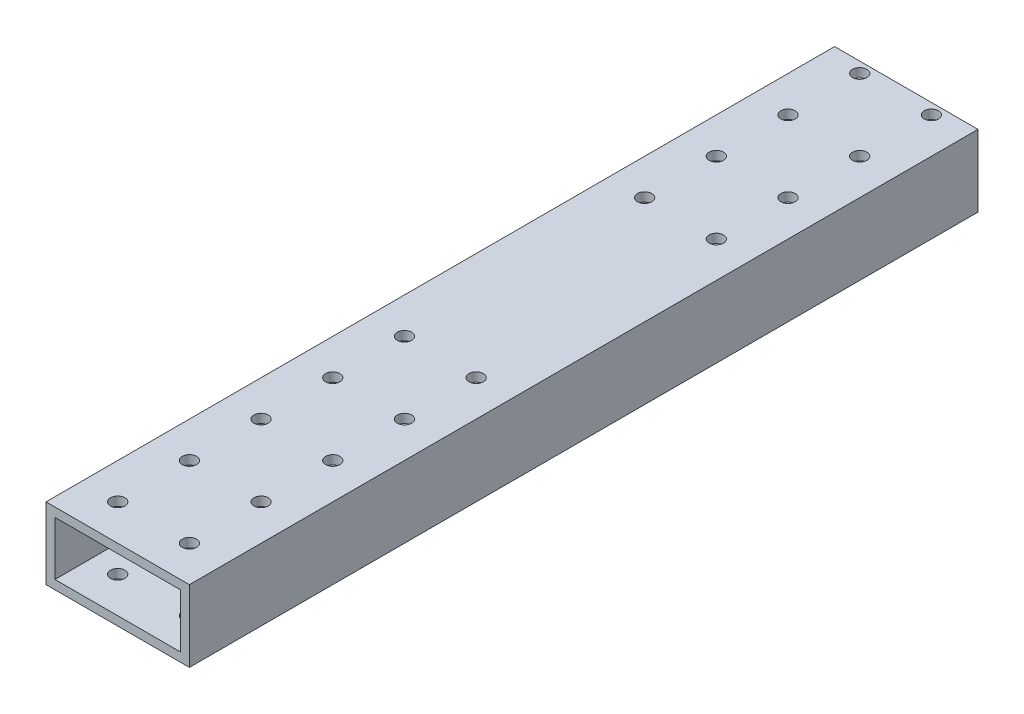
SolidWorks part; units mm, degrees
ref_plane "Front Plane" through (0, 0, 0) normal (0, 0, 1) x (1, 0, 0)
ref_plane "Top Plane" through (0, 0, 0) normal (0, 1, 0) x (1, 0, 0)
ref_plane "Right Plane" through (0, 0, 0) normal (1, 0, 0) x (0, 0, -1)
sketch "Sketch1" plane through (0, 0, 0) normal (0, 0, 1) x (1, 0, 0)
  line L1 (-25.4, -12.7) -> (25.4, -12.7)
  line L2 (-25.4, -12.7) -> (-25.4, 12.7)
  line L3 (-25.4, 12.7) -> (25.4, 12.7)
  line L4 (25.4, -12.7) -> (25.4, 12.7)
  line L5 (-25.4, -12.7) -> (25.4, 12.7) construction
  line L6 (-25.4, 12.7) -> (25.4, -12.7) construction
  line L7 (-22.225, -9.525) -> (22.225, -9.525)
  line L8 (-22.225, -9.525) -> (-22.225, 9.525)
  line L9 (-22.225, 9.525) -> (22.225, 9.525)
  line L10 (22.225, -9.525) -> (22.225, 9.525)
  line L11 (-22.225, -9.525) -> (22.225, 9.525) construction
  line L12 (-22.225, 9.525) -> (22.225, -9.525) construction
  point P0 (0, 0)
  point P6 (0, 0)
  dimension "D1" = 50.8
  dimension "D2" = 25.4
  dimension "D3" = 44.45
  dimension "D4" = 19.05
extrude "Boss-Extrude1" add sketch "Sketch1" along normal blind 279.4
sketch "Sketch2" plane through (0, 12.7, 0) normal (0, 1, 0) x (1, 0, 0)
  line L0 (-25.4, -139.7) -> (25.4, -139.7) construction
  line L1 (-25.4, -279.4) -> (-25.4, 0) construction
  line L2 (25.4, -279.4) -> (25.4, 0) construction
  line L3 (25.4, 0) -> (-25.4, 0) construction
  line L5 (25.4, -279.4) -> (-25.4, -279.4) construction
  circle A0 centre (-12.7, -3.81) radius 2.54
  circle A12 centre (-12.7, -266.7) radius 2.54
  circle A13 centre (12.7, -266.7) radius 2.54
  circle A14 centre (12.7, -241.3) radius 2.54
  circle A15 centre (12.7, -215.9) radius 2.54
  circle A16 centre (12.7, -190.5) radius 2.54
  circle A17 centre (12.7, -165.1) radius 2.54
  circle A18 centre (-12.7, -241.3) radius 2.54
  circle A19 centre (-12.7, -215.9) radius 2.54
  circle A20 centre (-12.7, -190.5) radius 2.54
  circle A21 centre (-12.7, -165.1) radius 2.54
  circle A22 centre (12.7, -3.81) radius 2.54
  circle A23 centre (12.7, -29.21) radius 2.54
  circle A24 centre (12.7, -54.61) radius 2.54
  circle A25 centre (-12.7, -29.21) radius 2.54
  circle A26 centre (-12.7, -54.61) radius 2.54
  circle A27 centre (-12.7, -80.01) radius 2.54
  circle A28 centre (12.7, -80.01) radius 2.54
  dimension "D1" = 3.81
  dimension "D5" = 12.7
  dimension "D2" = 12.7
  dimension "D6" = 12.7
  dimension "D7" = 2
  dimension "D8" = 5
  dimension "D3" = 2
  dimension "D4" = 4
extrude "Cut-Extrude1" cut sketch "Sketch2" against normal up to surface (25.4 mm away) up to face at (0, -12.7, 139.7)
